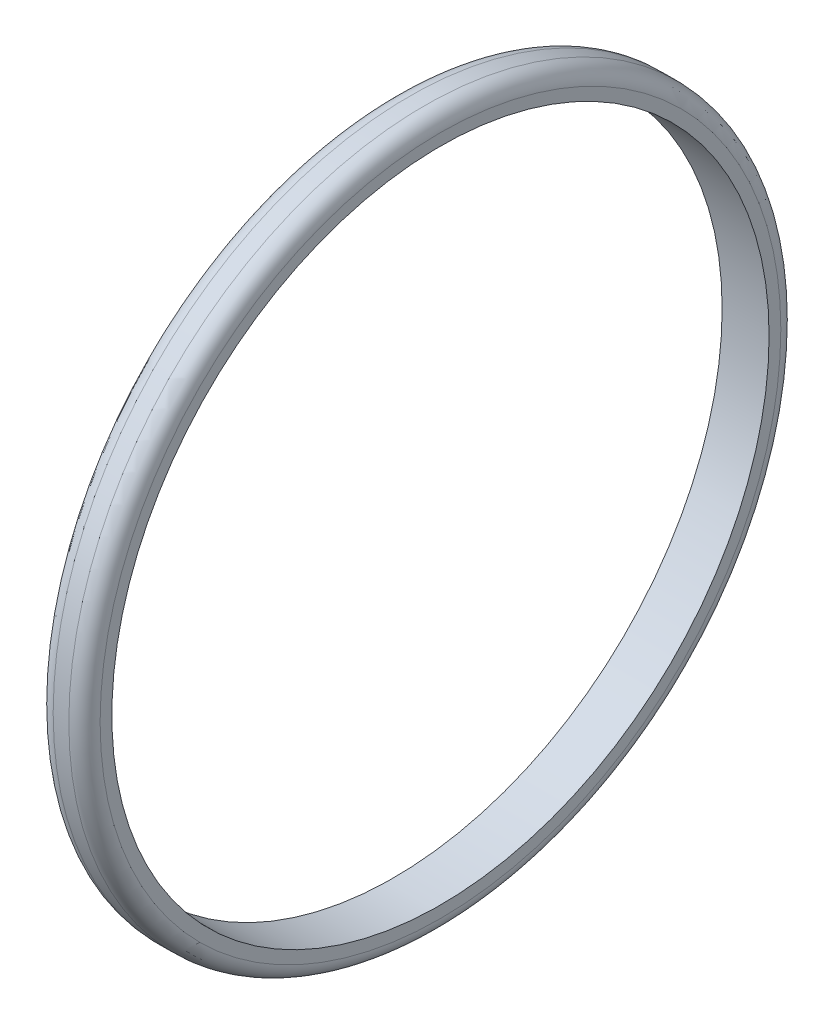
SolidWorks part; units mm, degrees
ref_plane "Front Plane" through (0, 0, 0) normal (0, 0, 1) x (1, 0, 0)
ref_plane "Top Plane" through (0, 0, 0) normal (0, 1, 0) x (1, 0, 0)
ref_plane "Right Plane" through (0, 0, 0) normal (1, 0, 0) x (0, 0, -1)
sketch "Sketch2" plane through (0, 0, 0) normal (1, 0, 0) x (0, 0, -1)
  circle A0 centre (0, 0) radius 42
  circle A1 centre (0, 0) radius 45.5
  dimension "D1" = 84
  dimension "D2" = 91
extrude "Boss-Extrude1" add sketch "Sketch2" along normal blind 6
fillet "Fillet1" radius 2 2 edges at (0, 0, -45.5) (6, 0, -45.5)
